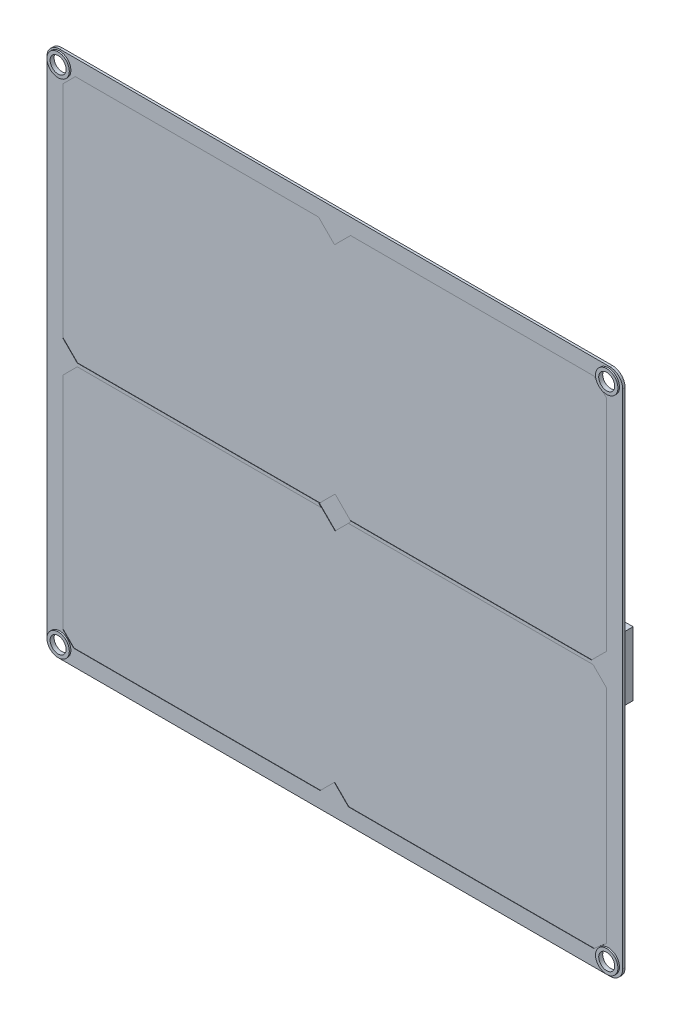
SolidWorks part; units mm, degrees
ref_plane "Plan de face" through (0, 0, 0) normal (0, 0, 1) x (1, 0, 0)
ref_plane "Plan de dessus" through (0, 0, 0) normal (0, 1, 0) x (1, 0, 0)
ref_plane "Plan de droite" through (0, 0, 0) normal (1, 0, 0) x (0, 0, -1)
sketch "Esquisse1" plane through (0, 0, 0) normal (0, 0, 1) x (1, 0, 0)
  line L1 (0, 0) -> (-360, 0)
  line L2 (0, 0) -> (0, 330)
  line L3 (0, 330) -> (-360, 330)
  line L4 (-360, 0) -> (-360, 330)
  dimension "D1" = 360
  dimension "D2" = 330
extrude "Boss.-Extru.1" add sketch "Esquisse1" along normal blind 1.5
sketch "Esquisse2" plane through (0, 0, 1.5) normal (0, 0, 1) x (1, 0, 0)
  line L0 (-360, 330) -> (-360, 0) construction
  line L1 (0, 330) -> (-360, 330) construction
  circle A0 centre (-352, 322) radius 5
  dimension "D1" = 10
  dimension "D2" = 8
  dimension "D3" = 8
extrude "Enlèv. mat.-Extru.1" cut sketch "Esquisse2" against normal blind 1.5
sketch "Esquisse3" plane through (0, 0, 1.5) normal (0, 0, 1) x (1, 0, 0)
  circle A0 centre (-352, 322) radius 5
  circle A1 centre (-352, 322) radius 7
  dimension "D1" = 10
  dimension "D2" = 14
extrude "Boss.-Extru.2" add sketch "Esquisse3" along normal blind 1
fillet "Congé2" radius 8 2 edges at (-360, 330, 0.75) (-360, 0, 0.75)
fillet "Congé4" radius 8 2 edges at (0, 0, 0.75) (0, 330, 0.75)
pattern_linear "Répétition linéaire2" count 2 spacing 343 along (1, 0, 0) count 2 spacing 314 along (0, -1, 0) of "Enlèv. mat.-Extru.1", "Boss.-Extru.2"
sketch "Esquisse4" plane through (0, 0, 1.5) normal (0, 0, 1) x (1, 0, 0)
  line L0 (-8, 330) -> (-352, 330) construction
  line L1 (-342.2248, 320) -> (-18.0728, 320)
  line L2 (-350, 312.2248) -> (-350, 16.7682)
  line L3 (-343.2318, 10) -> (-18.0728, 10)
  line L4 (-10, 311.9272) -> (-10, 16.7682)
  line L5 (-360, 322) -> (-360, 8) construction
  line L6 (0, 8) -> (0, 322) construction
  line L7 (-352, 0) -> (-8, 0) construction
  line L8 (-342.2248, 320) -> (-350, 312.2248)
  line L9 (-18.0728, 320) -> (-10, 311.9272)
  line L10 (-350, 16.7682) -> (-343.2318, 10)
  line L11 (-10, 16.7682) -> (-18.0728, 10)
  dimension "D1" = 10
  dimension "D2" = 10
  dimension "D3" = 10
  dimension "D4" = 10
extrude "Enlèv. mat.-Extru.2" cut sketch "Esquisse4" against normal blind 0.2
sketch "Esquisse5" plane through (0, 0, 1.3) normal (0, 0, 1) x (1, 0, 0)
  line L0 (-180, 330) -> (-180, 0) construction
  line L1 (-8, 330) -> (-352, 330) construction
  line L2 (-352, 0) -> (-8, 0) construction
  line L3 (-360, 165) -> (0, 165) construction
  line L4 (-360, 322) -> (-360, 8) construction
  line L5 (0, 8) -> (0, 322) construction
  line L8 (-180, 155) -> (-170, 165)
  line L9 (-170, 165) -> (-180, 175)
  line L10 (-180, 175) -> (-190, 165)
  line L11 (-190, 165) -> (-180, 155)
  dimension "D1" = 10
  dimension "D2" = 10
  dimension "D3" = 10
extrude "Enlèv. mat.-Extru.3" cut sketch "Esquisse5" against normal blind 0.2
sketch "Esquisse6" plane through (0, 0, 1.3) normal (0, 0, 1) x (1, 0, 0)
  line L0 (-180.1488, 320) -> (-180.6523, 10) construction
  line L1 (-18.0728, 320) -> (-342.2248, 320) construction
  line L2 (-343.2318, 10) -> (-18.0728, 10) construction
  line L3 (-350, 164.4965) -> (-10, 164.3477) construction
  line L4 (-350, 312.2248) -> (-350, 16.7682) construction
  line L5 (-10, 16.7682) -> (-10, 311.9272) construction
  line L6 (-190.1488, 320) -> (-180.1651, 310)
  line L7 (-180.1651, 310) -> (-170.1488, 320)
  line L8 (-18.0728, 320) -> (-342.2248, 320) construction
  line L9 (-350, 174.4921) -> (-340, 164.4921)
  line L10 (-340, 164.4921) -> (-350, 154.4921)
  line L11 (-350, 312.2248) -> (-350, 16.7682) construction
  line L12 (-190.1488, 320) -> (-170.1488, 320)
  line L13 (-350, 174.4921) -> (-350, 154.4921)
  line L14 (-190.285, 8.8532) -> (-180.2925, 18.8444)
  line L15 (-180.2925, 18.8444) -> (-170.285, 8.8356)
  line L16 (-190.285, 8.8532) -> (-170.285, 8.8356)
  dimension "D1" = 10
  dimension "D2" = 20
  dimension "D3" = 20
  dimension "D4" = 10
  dimension "D5" = 10
extrude "Boss.-Extru.3" add sketch "Esquisse6" along normal blind 0.2
sketch "Esquisse7" plane through (0, 0, 1.3) normal (0, 0, 1) x (1, 0, 0)
  line L0 (0, 165) -> (-46.6009, 165) construction
  line L1 (0, 8) -> (0, 322) construction
  line L2 (-10, 175) -> (-20, 165)
  line L3 (-10, 16.7682) -> (-10, 311.9272) construction
  line L4 (-20, 165) -> (-10, 155)
  line L5 (-10, 155) -> (-10, 175)
  line L6 (-10, 16.7682) -> (-10, 311.9272) construction
  dimension "D1" = 10
  dimension "D2" = 20
  dimension "D3" = 10
extrude "Boss.-Extru.4" add sketch "Esquisse7" along normal blind 0.2
sketch "Esquisse8" plane through (0, 0, 1.3) normal (0, 0, 1) x (1, 0, 0)
  line L11 (-341, 163.4921) -> (-188.4921, 163.4921)
  line L12 (-350, 154.4921) -> (-340, 164.4921) construction
  line L13 (-341, 165.4921) -> (-189.5079, 165.4921)
  line L14 (-340, 164.4921) -> (-350, 174.4921) construction
  line L15 (-341, 165.4921) -> (-341, 163.4921)
  line L16 (-6.9142, 165.4921) -> (-6.9142, 163.4921)
  line L17 (-340, 164.4921) -> (-302.1423, 164.4921) construction
  line L19 (-189.5079, 165.4921) -> (-190, 165)
  line L20 (-180, 175) -> (-190, 165) construction
  line L21 (-190, 165) -> (-188.4921, 163.4921)
  line L22 (-190, 165) -> (-180, 155) construction
  line L23 (-170.4921, 165.4921) -> (-170, 165)
  line L24 (-170, 165) -> (-180, 175) construction
  line L25 (-170, 165) -> (-171.5079, 163.4921)
  line L26 (-180, 155) -> (-170, 165) construction
  line L27 (-170.4921, 165.4921) -> (-6.9142, 165.4921)
  line L28 (-171.5079, 163.4921) -> (-6.9142, 163.4921)
  dimension "D1" = 1
extrude "Boss.-Extru.5" add sketch "Esquisse8" along normal blind 0.2
sketch "Esquisse9" plane through (0, 0, 0) normal (0, 0, -1) x (-1, 0, 0)
  line L0 (0, 165) -> (99.6008, 165) construction
  line L1 (0, 8) -> (0, 322) construction
  line L3 (5, 185) -> (45, 185)
  line L4 (5, 185) -> (5, 145)
  line L5 (5, 145) -> (45, 145)
  line L6 (45, 185) -> (45, 145)
  dimension "D1" = 40
  dimension "D2" = 40
  dimension "D3" = 20
  dimension "D4" = 5
extrude "Boss.-Extru.6" add sketch "Esquisse9" along normal blind 10
